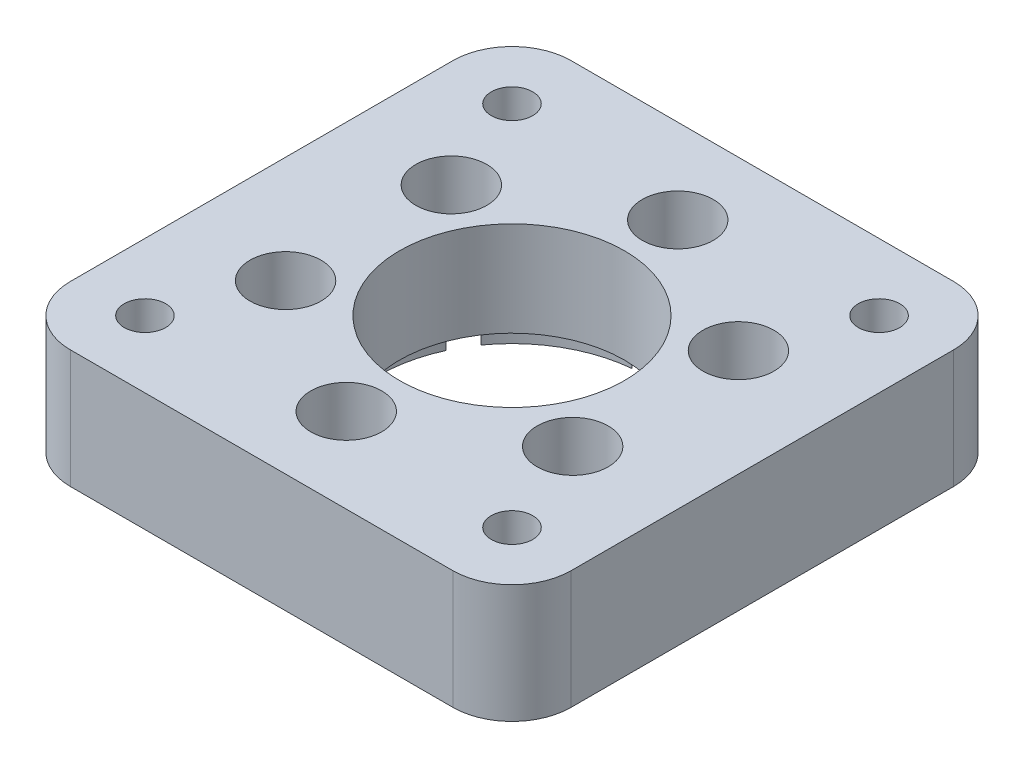
SolidWorks part; units mm, degrees
ref_plane "Front Plane" through (0, 0, 0) normal (0, 0, 1) x (1, 0, 0)
ref_plane "Top Plane" through (0, 0, 0) normal (0, 1, 0) x (1, 0, 0)
ref_plane "Right Plane" through (0, 0, 0) normal (1, 0, 0) x (0, 0, -1)
sketch "Sketch1" plane through (0, 0, 0) normal (0, 1, 0) x (1, 0, 0)
  line L1 (-21.15, 21.15) -> (21.15, 21.15)
  line L2 (-21.15, 21.15) -> (-21.15, -21.15)
  line L3 (-21.15, -21.15) -> (21.15, -21.15)
  line L4 (21.15, 21.15) -> (21.15, -21.15)
  line L5 (-21.15, 21.15) -> (21.15, -21.15) construction
  line L6 (-21.15, -21.15) -> (21.15, 21.15) construction
  point P0 (0, 0)
  dimension "D1" = 42.3
  dimension "D2" = 42.3
extrude "Boss-Extrude1" add sketch "Sketch1" along normal mid plane 10
fillet "Fillet1" radius 5 4 edges at (-21.15, 0, 21.15) (-21.15, 0, -21.15) (21.15, 0, -21.15) (21.15, 0, 21.15)
sketch "Sketch2" plane through (0, -5, 0) normal (0, -1, 0) x (1, 0, 0)
  line L1 (-15.5, -15.5) -> (15.5, -15.5) construction
  line L2 (-15.5, -15.5) -> (-15.5, 15.5) construction
  line L3 (-15.5, 15.5) -> (15.5, 15.5) construction
  line L4 (15.5, -15.5) -> (15.5, 15.5) construction
  line L5 (-15.5, -15.5) -> (15.5, 15.5) construction
  line L6 (-15.5, 15.5) -> (15.5, -15.5) construction
  circle A0 centre (-15.5, 15.5) radius 1.75
  circle A1 centre (15.5, 15.5) radius 1.75
  circle A2 centre (15.5, -15.5) radius 1.75
  circle A3 centre (-15.5, -15.5) radius 1.75
  point P0 (0, 0)
  dimension "D3" = 3.5
  dimension "D4" = 3.5
  dimension "D5" = 3.5
  dimension "D6" = 3.5
  dimension "D1" = 31
  dimension "D2" = 31
extrude "Cut-Extrude1" cut sketch "Sketch2" against normal through all
sketch "Sketch3" plane through (0, -5, 0) normal (0, -1, 0) x (1, 0, 0)
  circle A0 centre (0, 0) radius 11.25
  dimension "D1" = 22.5
extrude "Cut-Extrude2" cut sketch "Sketch3" against normal blind 2
sketch "Sketch4" plane through (0, -3, 0) normal (0, -1, 0) x (1, 0, 0)
  circle A0 centre (0, 0) radius 9.5
  dimension "D1" = 19
extrude "Cut-Extrude3" cut sketch "Sketch4" against normal through all
sketch "Sketch5" plane through (0, 5, 0) normal (0, 1, 0) x (1, 0, 0)
  line L0 (0, 0) -> (0, 21.15) construction
  line L1 (16.15, 21.15) -> (-16.15, 21.15) construction
  circle A0 centre (0, 14) radius 3
  dimension "D1" = 6
  dimension "D2" = 14
extrude "Cut-Extrude4" cut sketch "Sketch5" against normal through all
pattern_circular "CirPattern1" count 6 every 60 about axis through (0, 0, 0) along (0, 1, 0) of "Cut-Extrude4"
